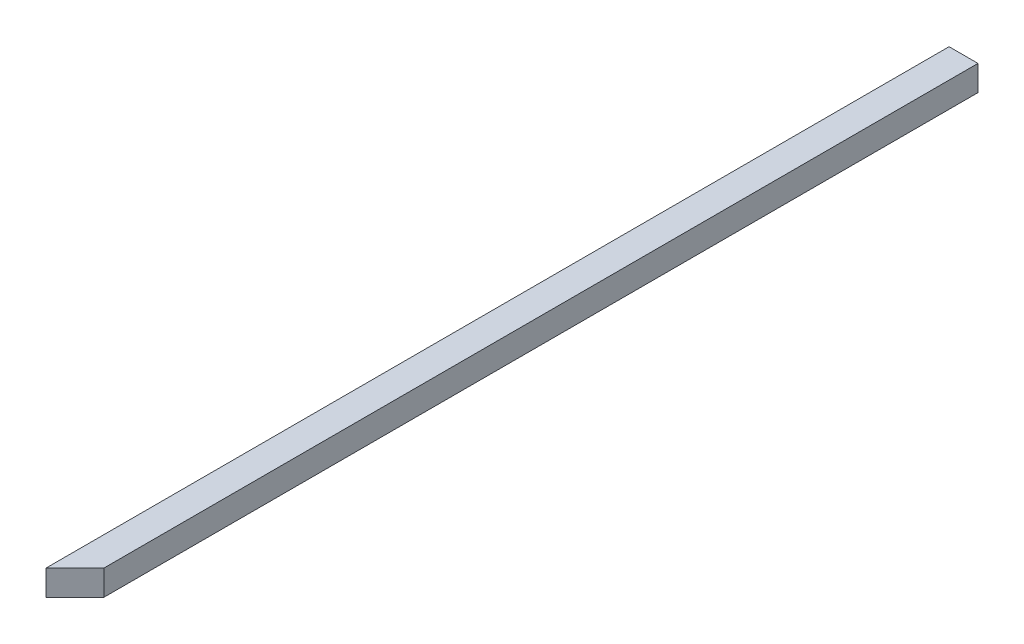
SolidWorks part; units mm, degrees
ref_plane "Alzado" through (0, 0, 0) normal (0, 0, 1) x (1, 0, 0)
ref_plane "Planta" through (0, 0, 0) normal (0, 1, 0) x (1, 0, 0)
ref_plane "Vista lateral" through (0, 0, 0) normal (1, 0, 0) x (0, 0, -1)
sketch "Croquis1" plane through (0, 0, 0) normal (0, 0, 1) x (1, 0, 0)
  line L1 (173.4777, -3.5) -> (169.4777, -3.5)
  line L2 (173.4777, -3.5) -> (173.4777, 0)
  line L3 (173.4777, 0) -> (169.4777, 0)
  line L4 (169.4777, -3.5) -> (169.4777, 0)
extrude "Saliente-Extruir1" add sketch "Croquis1" along normal up to vertex (120.8297 mm away)
sketch "Croquis2" plane through (0, -3.5, 0) normal (0, -1, 0) x (1, 0, 0)
  line L0 (169.4777, 120.8297) -> (169.4777, 124.8297)
  line L1 (169.4777, 124.8297) -> (173.4777, 120.8297)
  line L2 (173.4777, 120.8297) -> (169.4777, 120.8297)
extrude "Saliente-Extruir2" add sketch "Croquis2" against normal up to vertex (3.5 mm away) up to point (173.4777, 0, 120.8297)
